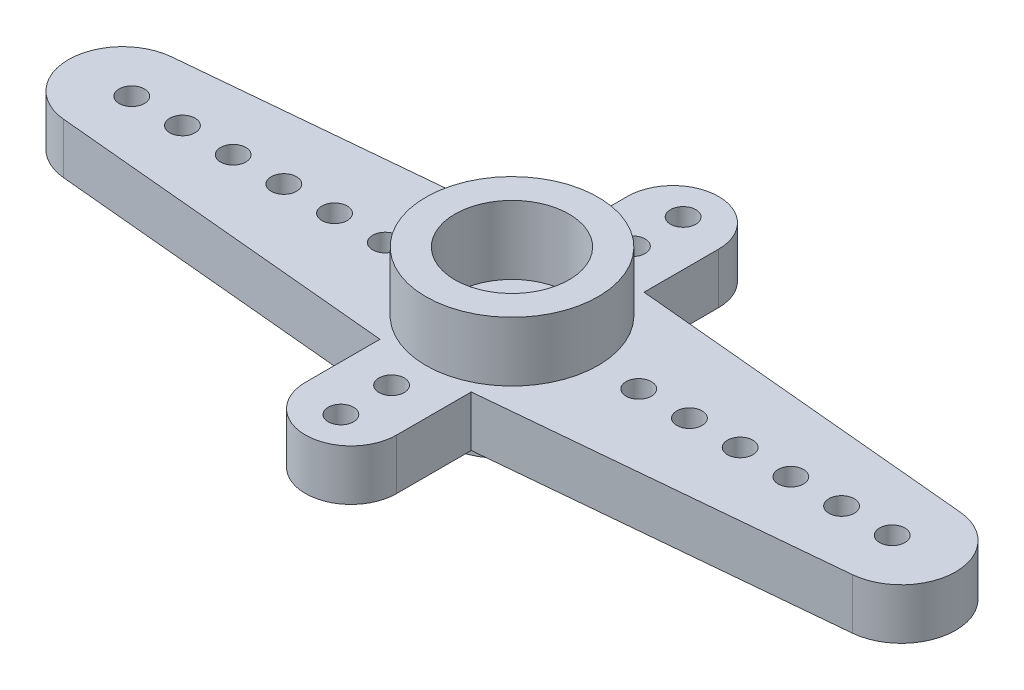
SolidWorks part; units mm, degrees
ref_plane "前视基准面" through (0, 0, 0) normal (0, 0, 1) x (1, 0, 0)
ref_plane "上视基准面" through (0, 0, 0) normal (0, 1, 0) x (1, 0, 0)
ref_plane "右视基准面" through (0, 0, 0) normal (1, 0, 0) x (0, 0, -1)
sketch "草图1" plane through (0, 0, 0) normal (0, 1, 0) x (1, 0, 0)
  circle A0 centre (0, 0) radius 2.25
  circle A1 centre (0, 0) radius 3.4
extrude "凸台-拉伸1" add sketch "草图1" along normal blind 4.85
sketch "草图2" plane through (0, 0, 0) normal (0, 1, 0) x (1, 0, 0)
  line L0 (-15, 0) -> (15, 0) construction
  line L1 (0, 6.75) -> (0, -6.75) construction
  line L16 (1.8, 3.4079) -> (1.8, 6.35)
  line L17 (-1.8, 6.35) -> (-1.8, 3.4079)
  line L18 (-1.8, 3.4079) -> (-15.5584, 2.1303)
  line L19 (-15.5584, -2.1303) -> (-1.8, -3.4079)
  line L20 (-1.8, -3.4079) -> (-1.8, -6.35)
  line L21 (1.8, -6.35) -> (1.8, -3.4079)
  line L22 (1.8, -3.4079) -> (15.5584, -2.1303)
  line L23 (15.5584, 2.1303) -> (1.8, 3.4079)
  circle A0 centre (0, 0) radius 2.25 construction
  circle A1 centre (0, 0) radius 2.25
  circle A2 centre (0, -6.75) radius 0.5
  arc A8 (1.8, 6.35) -> (-1.8, 6.35) centre (0, 6.35) ccw
  arc A9 (-15.5584, 2.1303) -> (-15.5584, -2.1303) centre (-15.3605, 0) ccw
  arc A10 (-1.8, -6.35) -> (1.8, -6.35) centre (0, -6.35) ccw
  arc A11 (15.5584, -2.1303) -> (15.5584, 2.1303) centre (15.3605, 0) ccw
  circle A12 centre (0, -4.75) radius 0.5
  circle A14 centre (15, 0) radius 0.5
  circle A16 centre (13, 0) radius 0.5
  circle A18 centre (11, 0) radius 0.5
  circle A20 centre (9, 0) radius 0.5
  circle A22 centre (7, 0) radius 0.5
  circle A24 centre (5, 0) radius 0.5
  circle A26 centre (0, 6.75) radius 0.5
  circle A28 centre (0, 4.75) radius 0.5
  circle A30 centre (-5, 0) radius 0.5
  circle A32 centre (-7, 0) radius 0.5
  circle A34 centre (-9, 0) radius 0.5
  circle A36 centre (-11, 0) radius 0.5
  circle A38 centre (-13, 0) radius 0.5
  circle A40 centre (-15, 0) radius 0.5
  dimension "D9" = 1
  dimension "D1" = 2
  dimension "D2" = 2
  dimension "D3" = 2
  dimension "D4" = 2
  dimension "D5" = 2
  dimension "D6" = 15
  dimension "D7" = 15
  dimension "D8" = 13.5
  dimension "D10" = 2
  dimension "D11" = 2
  dimension "D12" = 2
  dimension "D13" = 2
  dimension "D14" = 2
  dimension "D15" = 2
  dimension "D16" = 2
extrude "凸台-拉伸2" add sketch "草图2" along normal blind 2 from offset 0.5
sketch "草图3" plane through (0, 0, 0) normal (0, 1, 0) x (1, 0, 0)
  circle A0 centre (0, 0) radius 1.15
  circle A1 centre (0, 0) radius 2.25 construction
  circle A2 centre (0, 0) radius 2.25
  dimension "D1" = 2.3
extrude "凸台-拉伸3" add sketch "草图3" along normal blind 0.9 from offset 1.25
